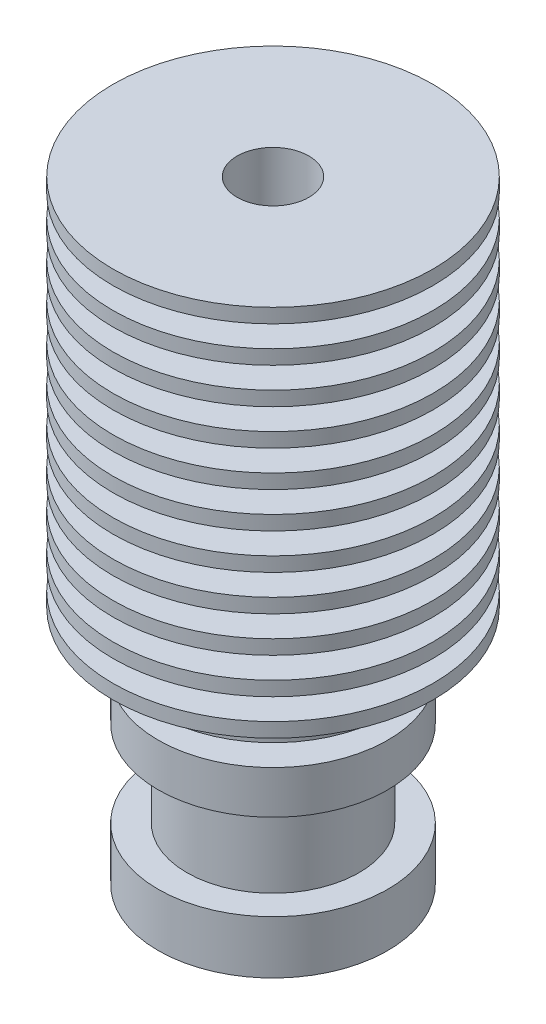
SolidWorks part; units mm, degrees
material "6061-O (SS)"
ref_plane "Plan de face" through (0, 0, 0) normal (0, 0, 1) x (1, 0, 0)
ref_plane "Plan de dessus" through (0, 0, 0) normal (0, 1, 0) x (1, 0, 0)
ref_plane "Plan de droite" through (0, 0, 0) normal (1, 0, 0) x (0, 0, -1)
ref_plane "Plan1" through (0, 14.2, 0) normal (0, 1, 0) x (1, 0, 0)
ref_plane "Plan2" through (0, 16.7, 0) normal (0, 1, 0) x (1, 0, 0)
sketch "Esquisse1" plane through (0, 0, 0) normal (0, 1, 0) x (1, 0, 0)
  circle A1 centre (0, 0) radius 8
  dimension "D2" = 16
extrude "Boss.-Extru.1" add sketch "Esquisse1" along normal blind 3.7
sketch "Esquisse2" plane through (0, 3.7, 0) normal (0, 1, 0) x (1, 0, 0)
  circle A1 centre (0, 0) radius 6
  dimension "D2" = 12
extrude "Boss.-Extru.2" add sketch "Esquisse2" along normal blind 6
sketch "Esquisse3" plane through (0, 9.7, 0) normal (0, 1, 0) x (1, 0, 0)
  circle A0 centre (0, 0) radius 3.25
  circle A1 centre (0, 0) radius 8
  dimension "D1" = 6.5
  dimension "D2" = 16
extrude "Boss.-Extru.3" add sketch "Esquisse3" along normal blind 3
sketch "Esquisse4" plane through (0, 12.7, 0) normal (0, 1, 0) x (1, 0, 0)
  circle A1 centre (0, 0) radius 4.5
  dimension "D2" = 9
extrude "Boss.-Extru.4" add sketch "Esquisse4" along normal blind 30 draft 3 draft outward yes
sketch "Esquisse5" plane through (0, 42.7, 0) normal (0, 1, 0) x (1, 0, 0)
  circle A0 centre (0, 0) radius 2.1
  dimension "D1" = 4.2
extrude "Enlèv. mat.-Extru.1" cut sketch "Esquisse5" against normal up to next
hole_wizard "Trou taraudé M61" positions "Esquisse8" profile "Esquisse7" tap size "M6" standard "Iso"
sketch "Esquisse8" plane through (0, 42.7, 0) normal (0, 1, 0) x (1, 0, 0)
  point P0 (0, 0)
sketch "Esquisse7" plane through (0, 42.7, 0) normal (1, 0, 0) x (0, 0, 1)
  line L0 (0, 0) -> (0, 19.4022)
  line L1 (0, 19.4022) -> (2.5, 17.9)
  line L2 (2.5, 17.9) -> (2.5, 0)
  line L5 (2.5, 0) -> (0, 0)
  line L10 (0, 19.4022) -> (-2.5, 17.9) construction
  line L11 (0, -6.35) -> (0, 107.95) construction
  dimension "Diamètre du trou pour taraudage" = 5
  dimension "Profondeur du trou pour taraudage" = 17.9
  dimension "Angle de pointe" = 118
cosmetic thread "Filetage de perçage1" parameters "D1"=14.9, "D2"=7.723
sketch "Esquisse9" plane through (0, 14.2, 0) normal (0, 1, 0) x (1, 0, 0)
  circle A0 centre (0, 0) radius 8
  circle A1 centre (0, 0) radius 4.25
  dimension "D1" = 16
  dimension "D2" = 8.5
extrude "Boss.-Extru.5" add sketch "Esquisse9" along normal blind 1
sketch "Esquisse10" plane through (0, 16.7, 0) normal (0, 1, 0) x (1, 0, 0)
  circle A0 centre (0, 0) radius 4.25
  circle A1 centre (0, 0) radius 11.15
  dimension "D1" = 8.5
  dimension "D2" = 22.3
extrude "Boss.-Extru.6" add sketch "Esquisse10" along normal blind 1
sketch "Esquisse11" plane through (0, 0, 0) normal (0, 0, 1) x (1, 0, 0)
  line L0 (0, 44.0354) -> (0, -2.7213) construction
pattern_linear "Répétition linéaire1" count 11 spacing 2.5 along (0, 1, 0) of "Boss.-Extru.6"
hole_wizard "Trou taraudé M51" positions "Esquisse13" profile "Esquisse12" tap size "M5" standard "Iso"
sketch "Esquisse13" plane through (0, 0, 0) normal (0, -1, 0) x (-1, 0, 0)
  point P0 (0, 0)
sketch "Esquisse12" plane through (0, 0, 0) normal (1, 0, 0) x (0, 0, -1)
  line L0 (0, 0) -> (0, 13.6618)
  line L1 (0, 13.6618) -> (2.1, 12.4)
  line L2 (2.1, 12.4) -> (2.1, 0)
  line L5 (2.1, 0) -> (0, 0)
  line L10 (0, 13.6618) -> (-2.1, 12.4) construction
  line L11 (0, -6.35) -> (0, 107.95) construction
  dimension "Diamètre du trou pour taraudage" = 4.2
  dimension "Profondeur du trou pour taraudage" = 12.4
  dimension "Angle de pointe" = 118
cosmetic thread "Filetage de perçage2" parameters "D1"=9.7, "D2"=5
